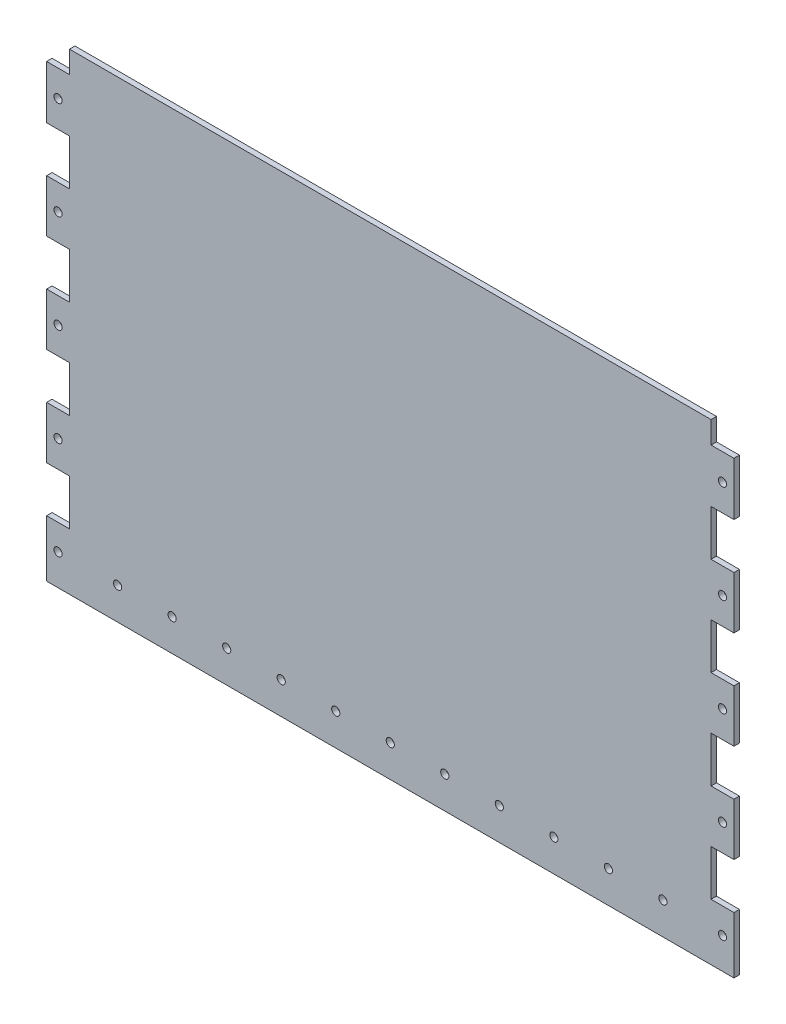
SolidWorks part; units mm, degrees
material "FR4"
ref_plane "前视基准面" through (0, 0, 0) normal (0, 0, 1) x (1, 0, 0)
ref_plane "上视基准面" through (0, 0, 0) normal (0, 1, 0) x (1, 0, 0)
ref_plane "右视基准面" through (0, 0, 0) normal (1, 0, 0) x (0, 0, -1)
sketch "草图1" plane through (0, 0, 0) normal (0, 0, 1) x (1, 0, 0)
  line L1 (126.05, -83.1) -> (-126.05, -83.1)
  line L2 (126.05, -83.1) -> (126.05, 83.1)
  line L3 (126.05, 83.1) -> (-126.05, 83.1)
  line L4 (-126.05, -83.1) -> (-126.05, 83.1)
  line L5 (126.05, -83.1) -> (-126.05, 83.1) construction
  line L6 (126.05, 83.1) -> (-126.05, -83.1) construction
  point P0 (0, 0)
  dimension "D1" = 252.1
  dimension "D2" = 166.2
extrude "凸台-拉伸1" add sketch "草图1" along normal mid plane 2
sketch "草图2" plane through (0, 0, 1) normal (0, 0, 1) x (1, 0, 0)
  line L5 (0, 0) -> (144.4976, 0) construction
  line L6 (0, 0) -> (0, 93.1697) construction
  line L20 (-126.05, 83.1) -> (-126.05, -83.1) construction
  line L21 (-126.05, 63.5) -> (-117.65, 63.5)
  line L23 (-126.05, 63.5) -> (-126.05, 46.7)
  line L28 (-126.05, 46.7) -> (-117.65, 46.7)
  line L29 (-117.65, 63.5) -> (-117.65, 46.7)
  line L30 (126.05, 83.1) -> (-126.05, 83.1) construction
  line L40 (-126.05, 27.5) -> (-117.65, 27.5)
  line L41 (-126.05, 27.5) -> (-126.05, 10.7)
  line L42 (-126.05, 10.7) -> (-117.65, 10.7)
  line L43 (-117.65, 27.5) -> (-117.65, 10.7)
  line L44 (-126.05, -8.5) -> (-117.65, -8.5)
  line L45 (-126.05, -8.5) -> (-126.05, -25.3)
  line L46 (-126.05, -25.3) -> (-117.65, -25.3)
  line L47 (-117.65, -8.5) -> (-117.65, -25.3)
  line L48 (-126.05, -44.5) -> (-117.65, -44.5)
  line L49 (-126.05, -44.5) -> (-126.05, -61.3)
  line L50 (-126.05, -61.3) -> (-117.65, -61.3)
  line L51 (-117.65, -44.5) -> (-117.65, -61.3)
  line L52 (-126.05, 63.5) -> (-126.05, 27.5) construction
  line L53 (126.05, 63.5) -> (126.05, 27.5) construction
  line L54 (117.65, -44.5) -> (117.65, -61.3)
  line L55 (126.05, -61.3) -> (117.65, -61.3)
  line L56 (126.05, -44.5) -> (126.05, -61.3)
  line L57 (126.05, -44.5) -> (117.65, -44.5)
  line L58 (117.65, -8.5) -> (117.65, -25.3)
  line L59 (126.05, -25.3) -> (117.65, -25.3)
  line L60 (126.05, -8.5) -> (126.05, -25.3)
  line L61 (126.05, -8.5) -> (117.65, -8.5)
  line L62 (117.65, 27.5) -> (117.65, 10.7)
  line L63 (126.05, 10.7) -> (117.65, 10.7)
  line L64 (126.05, 27.5) -> (126.05, 10.7)
  line L65 (126.05, 27.5) -> (117.65, 27.5)
  line L66 (117.65, 63.5) -> (117.65, 46.7)
  line L67 (126.05, 46.7) -> (117.65, 46.7)
  line L68 (126.05, 63.5) -> (126.05, 46.7)
  line L69 (126.05, 63.5) -> (117.65, 63.5)
  line L70 (-121.85, 83.1) -> (-121.85, 63.5) construction
  line L71 (-121.85, 73.3) -> (-121.85, 37.3) construction
  line L72 (126.05, 77.9891) -> (126.05, 86.2525) construction
  line L73 (-126.05, 83.1891) -> (126.05, 83.1891)
  line L74 (-126.05, 83.1891) -> (-126.05, 82.9891)
  line L75 (-126.05, 82.9891) -> (126.05, 82.9891)
  line L76 (126.05, 83.1891) -> (126.05, 82.9891)
  line L77 (126.05, -83.1) -> (126.05, 83.1) construction
  line L78 (-126.05, -83.1) -> (126.05, -83.1)
  line L79 (-126.05, -83.1) -> (-126.05, -82.1)
  line L80 (-126.05, -82.1) -> (126.05, -82.1)
  line L81 (126.05, -83.1) -> (126.05, -82.1)
  circle A0 centre (-121.85, 73.3) radius 1.5
  circle A1 centre (-121.85, 37.3) radius 1.5
  circle A2 centre (-121.85, 1.3) radius 1.5
  circle A3 centre (-121.85, -34.7) radius 1.5
  circle A4 centre (-121.85, -70.7) radius 1.5
  circle A5 centre (121.85, -70.7) radius 1.5
  circle A6 centre (121.85, -34.7) radius 1.5
  circle A7 centre (121.85, 1.3) radius 1.5
  circle A8 centre (121.85, 37.3) radius 1.5
  circle A9 centre (121.85, 73.3) radius 1.5
  dimension "D4" = 4
  dimension "D6" = 3
  dimension "D1" = 8.4
  dimension "D2" = 19.6
  dimension "D3" = 16.8
  dimension "D5" = 36
  dimension "D8" = 36
  dimension "D9" = 0.2
  dimension "D10" = 1
  dimension "D7" = 5
extrude "Cut-Extrude1" cut sketch "草图2" against normal blind 10
sketch "Sketch1" plane through (0, 0, 1) normal (0, 0, 1) x (1, 0, 0)
  circle A0 centre (100, -70.35) radius 1.5 construction
  circle A1 centre (80, -70.35) radius 1.5 construction
  circle A2 centre (60, -70.35) radius 1.5 construction
  circle A3 centre (40, -70.35) radius 1.5 construction
  circle A4 centre (20, -70.35) radius 1.5 construction
  circle A5 centre (0, -70.35) radius 1.5 construction
  circle A6 centre (-20, -70.35) radius 1.5 construction
  circle A7 centre (-40, -70.35) radius 1.5 construction
  circle A8 centre (-60, -70.35) radius 1.5 construction
  circle A9 centre (-80, -70.35) radius 1.5 construction
  circle A10 centre (-100, -70.35) radius 1.5 construction
  circle A11 centre (100, -70.35) radius 1.5
  circle A12 centre (80, -70.35) radius 1.5
  circle A13 centre (60, -70.35) radius 1.5
  circle A14 centre (40, -70.35) radius 1.5
  circle A15 centre (20, -70.35) radius 1.5
  circle A16 centre (0, -70.35) radius 1.5
  circle A17 centre (-20, -70.35) radius 1.5
  circle A18 centre (-40, -70.35) radius 1.5
  circle A19 centre (-60, -70.35) radius 1.5
  circle A20 centre (-80, -70.35) radius 1.5
  circle A21 centre (-100, -70.35) radius 1.5
extrude "Cut-Extrude2" cut sketch "Sketch1" against normal blind 10
sketch "Sketch2" plane through (0, 0, 1) normal (0, 0, 1) x (1, 0, 0)
  line L1 (-117.65, 82.9891) -> (117.65, 82.9891)
  line L2 (-117.65, 82.9891) -> (-117.65, 91.0891)
  line L3 (-117.65, 91.0891) -> (117.65, 91.0891)
  line L4 (117.65, 82.9891) -> (117.65, 91.0891)
  line L6 (118.05, 91.4891) -> (118.05, 83.1891) construction
  line L7 (-118.05, 91.4891) -> (-118.05, 83.1891) construction
  line L8 (140.24, 91.4891) -> (-126.05, 91.4891) construction
  line L9 (-126.05, 82.9891) -> (126.05, 82.9891) construction
  dimension "D1" = 0.4
  dimension "D2" = 0.4
  dimension "D3" = 0.4
extrude "Boss-Extrude1" add sketch "Sketch2" against normal blind 2
